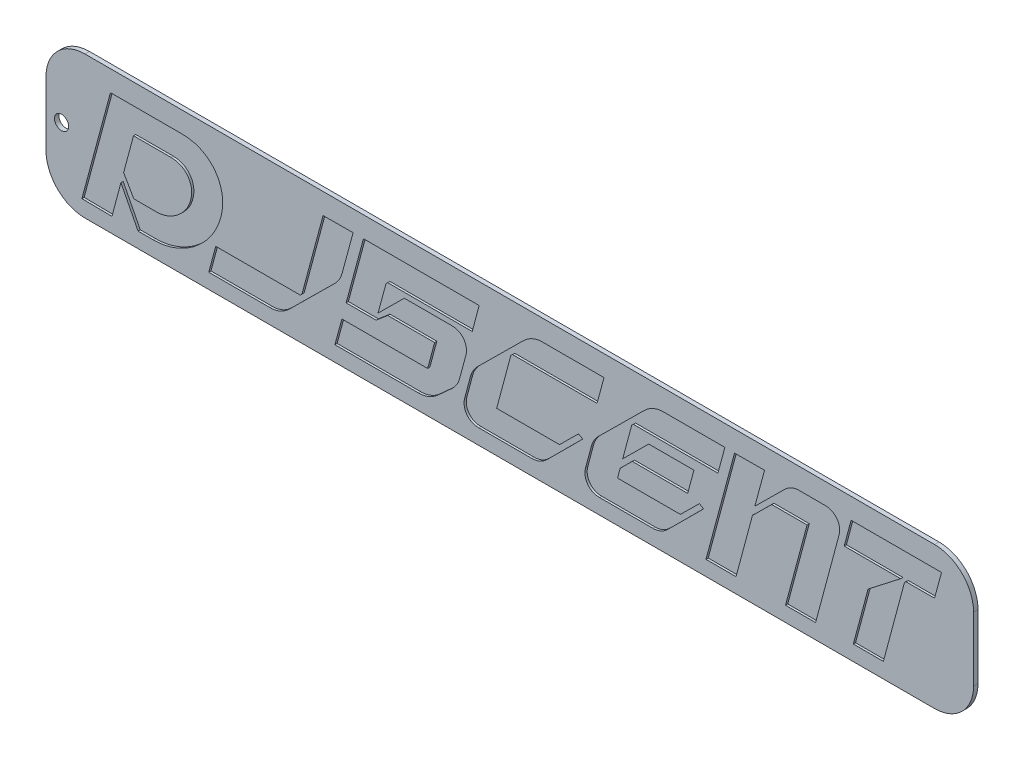
SolidWorks part; units mm, degrees
ref_plane "Front Plane" through (0, 0, 0) normal (0, 0, 1) x (1, 0, 0)
ref_plane "Top Plane" through (0, 0, 0) normal (0, 1, 0) x (1, 0, 0)
ref_plane "Right Plane" through (0, 0, 0) normal (1, 0, 0) x (0, 0, -1)
sketch "Sketch1" plane through (0, 0, 0) normal (0, 0, 1) x (1, 0, 0)
  line L0 (-30.7041, 40.0538) -> (-19.5594, 40.0538) construction
  line L1 (-2.7641, 90.9366) -> (605.6156, 90.9366)
  line L2 (-30.7041, 62.9966) -> (-30.7041, 17.1109)
  line L3 (-2.7641, -10.8291) -> (605.6156, -10.8291)
  line L4 (633.5556, 62.9966) -> (633.5556, 17.1109)
  arc A0 (605.6156, -10.8291) -> (633.5556, 17.1109) centre (605.6156, 17.1109) ccw
  arc A1 (605.6156, 90.9366) -> (633.5556, 62.9966) centre (605.6156, 62.9966) cw
  arc A2 (-30.7041, 17.1109) -> (-2.7641, -10.8291) centre (-2.7641, 17.1109) ccw
  arc A3 (-2.7641, 90.9366) -> (-30.7041, 62.9966) centre (-2.7641, 62.9966) ccw
  circle A4 centre (-19.5594, 40.0538) radius 5.08
  text T0 "dj5cent" font "Sterion" height 76.2
  dimension "D1" = 27.94
extrude "Boss-Extrude1" add sketch "Sketch1" along normal blind 3.175 contours L4 L1 L2 L3
sketch "Sketch2" plane through (0, 0, 3.175) normal (0, 0, 1) x (1, 0, 0)
  text T0 "dj5cent" font "Sterion" height 76.2
extrude "Cut-Extrude1" cut sketch "Sketch2" against normal blind 1.5875
